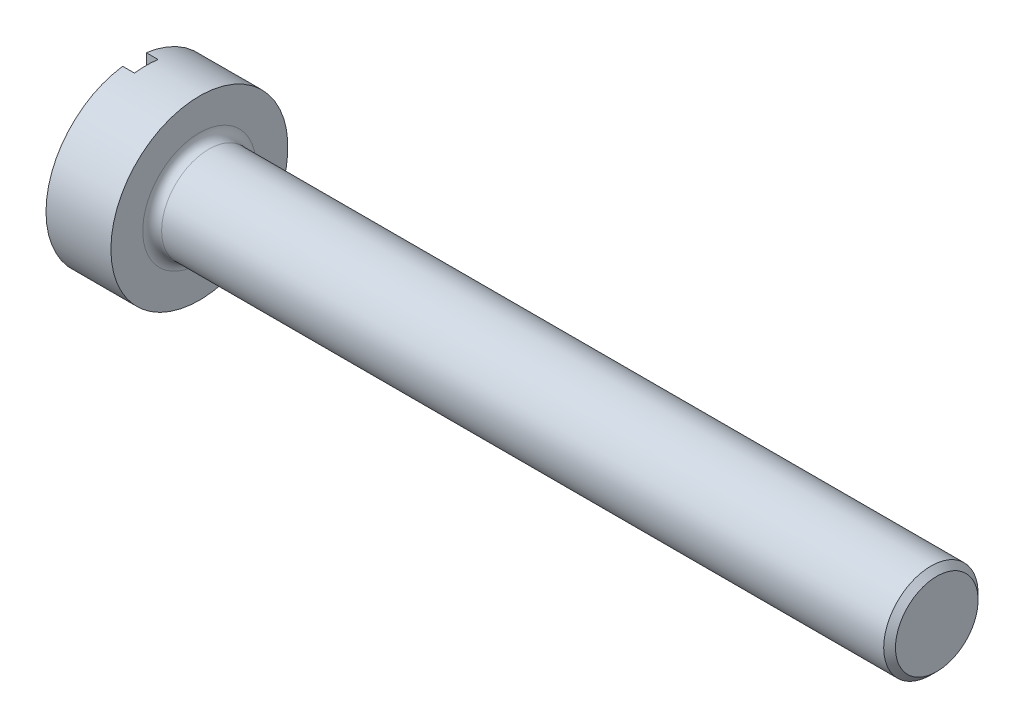
SolidWorks part; units mm, degrees
ref_plane "Front Plane" through (0, 0, 0) normal (0, 0, 1) x (1, 0, 0)
ref_plane "Top Plane" through (0, 0, 0) normal (0, 1, 0) x (1, 0, 0)
ref_plane "Right Plane" through (0, 0, 0) normal (1, 0, 0) x (0, 0, -1)
sketch "Sketch1" plane through (0, 0, 0) normal (0, 0, 1) x (1, 0, 0)
  line L0 (0, 0) -> (0, 1.5)
  line L1 (0, 1.5) -> (1.1, 1.5)
  line L2 (1.1, 1.5) -> (1.1, 0)
  line L3 (0, 0) -> (13.6, 0)
  line L4 (13.6, 0) -> (13.6, 0.8)
  line L5 (13.6, 0.8) -> (1.1, 0.8)
  dimension "D1" = 1.5
  dimension "D2" = 1.1
  dimension "D3" = 12.5
revolve "Revolve1" add sketch "Sketch1" angle 360 about L3
chamfer "Chamfer1" distance 0.1 angle 45 1 edges at (13.6, 0, 0.8)
fillet "Fillet1" radius 0.16 1 edges at (1.1, 0, 0.8)
sketch "Sketch2" plane through (0, 0, 0) normal (0, 1, 0) x (1, 0, 0)
  line L1 (0, 0) -> (0.2, 0)
  line L2 (0, 0) -> (0, 0.2)
  line L3 (0, 0.2) -> (0.2, 0.2)
  line L4 (0.2, 0) -> (0.2, 0.2)
  line L5 (0, 0) -> (0.2, 0)
  line L6 (0, 0) -> (0, -0.2)
  line L7 (0, -0.2) -> (0.2, -0.2)
  line L8 (0.2, 0) -> (0.2, -0.2)
extrude "Extrude1" cut sketch "Sketch2" against normal through all both and the other way through all contours L8 L1 L6 L7 | L1 L4 L3 L2
